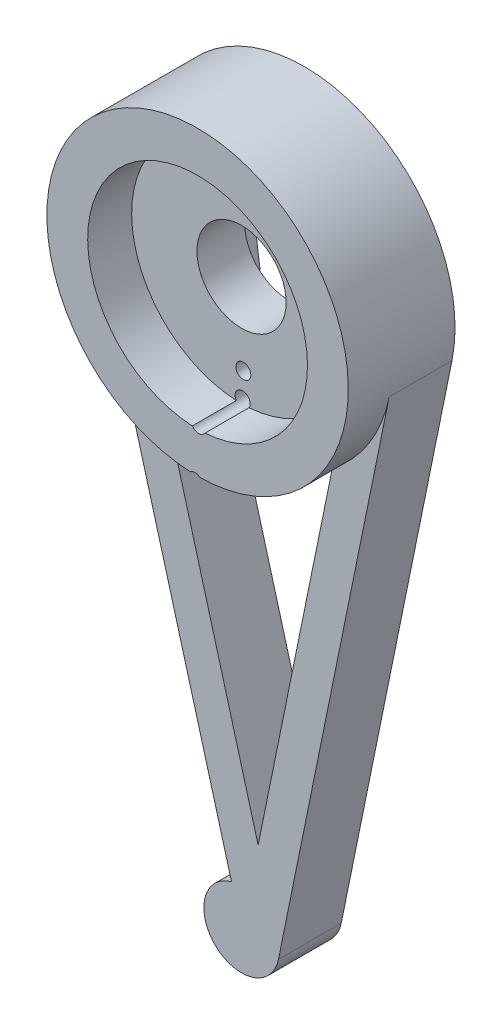
SolidWorks part; units mm, degrees
ref_plane "Front Plane" through (0, 0, 0) normal (0, 0, 1) x (1, 0, 0)
ref_plane "Top Plane" through (0, 0, 0) normal (0, 1, 0) x (1, 0, 0)
ref_plane "Right Plane" through (0, 0, 0) normal (1, 0, 0) x (0, 0, -1)
sketch "Sketch1" plane through (0, 0, 0) normal (0, 0, 1) x (1, 0, 0)
  line L0 (0, 0) -> (0, -14.7957) construction
  line L1 (0, 0) -> (27.0378, 0) construction
  line L2 (2.9394, -45.6) -> (11.7576, -2.4)
  line L3 (-11.5655, -3.2) -> (-0.8, -42.1086)
  line L4 (1.3215, -38.5261) -> (7.2235, -9.6124)
  line L5 (-6.6785, -9.6124) -> (1.3215, -38.5261)
  arc A0 (11.7576, -2.4) -> (-11.5655, -3.2) centre (0, 0) ccw
  arc A1 (-0.8, -42.1086) -> (2.9394, -45.6) centre (0, -45) ccw
  circle A2 centre (0, 0) radius 3.55
  arc A7 (-6.6785, -9.6124) -> (7.2235, -9.6124) centre (0.2725, -1.634) ccw
  dimension "D2" = 12
  dimension "D3" = 3
  dimension "D4" = 7.1
  dimension "D1" = 45
  dimension "D5" = 3
  dimension "D6" = 3
  dimension "30" = 30
extrude "Boss-Extrude1" add sketch "Sketch1" along normal blind 5
sketch "Sketch2" plane through (0, 0, 0) normal (0, 0, -1) x (-1, 0, 0)
  line L0 (-1.9821, -15.2667) -> (-3.9643, -0.5333)
  line L1 (3.9643, -0.5333) -> (1.9821, -15.2667)
  arc A0 (3.9643, -0.5333) -> (-3.9643, -0.5333) centre (0, 0) ccw
  arc A1 (-1.9821, -15.2667) -> (1.9821, -15.2667) centre (0, -15) ccw
  dimension "D1" = 8
  dimension "D2" = 4
  dimension "D3" = 15
extrude "Cut-Extrude1" cut sketch "Sketch2" against normal blind 1.2
sketch "Sketch3" plane through (0, 0, 5) normal (0, 0, 1) x (1, 0, 0)
  line L2 (-11.5655, -3.2) -> (-0.8, -42.1086)
  line L3 (2.9394, -45.6) -> (11.7576, -2.4)
  circle A0 centre (0, 0) radius 8.75
  arc A2 (11.7576, -2.4) -> (-11.5655, -3.2) centre (0, 0) ccw
  arc A3 (-0.8, -42.1086) -> (2.9394, -45.6) centre (0, -45) ccw
  arc A4 (11.7576, -2.4) -> (-11.5655, -3.2) centre (0, 0) ccw
  arc A7 (-11.5655, -3.2) -> (11.7576, -2.4) centre (0, 0) ccw
  dimension "D2" = 17.5
  dimension "D1" = 0
extrude "Boss-Extrude2" add sketch "Sketch3" along normal blind 3.5
sketch "Sketch5" plane through (0, 0, 1.2) normal (0, 0, -1) x (-1, 0, 0)
  line L0 (-0.3338, 0.6089) -> (0.2652, -21.3024) construction
  circle A1 centre (-0.1418, -6.414) radius 0.6
  circle A2 centre (-0.0862, -8.414) radius 0.6
  circle A5 centre (0.2324, -14.4481) radius 0.6
  circle A6 centre (0.2003, -12.4484) radius 0.6
  dimension "D1" = 2
extrude "Cut-Extrude2" cut sketch "Sketch5" against normal through all both and the other way through all
